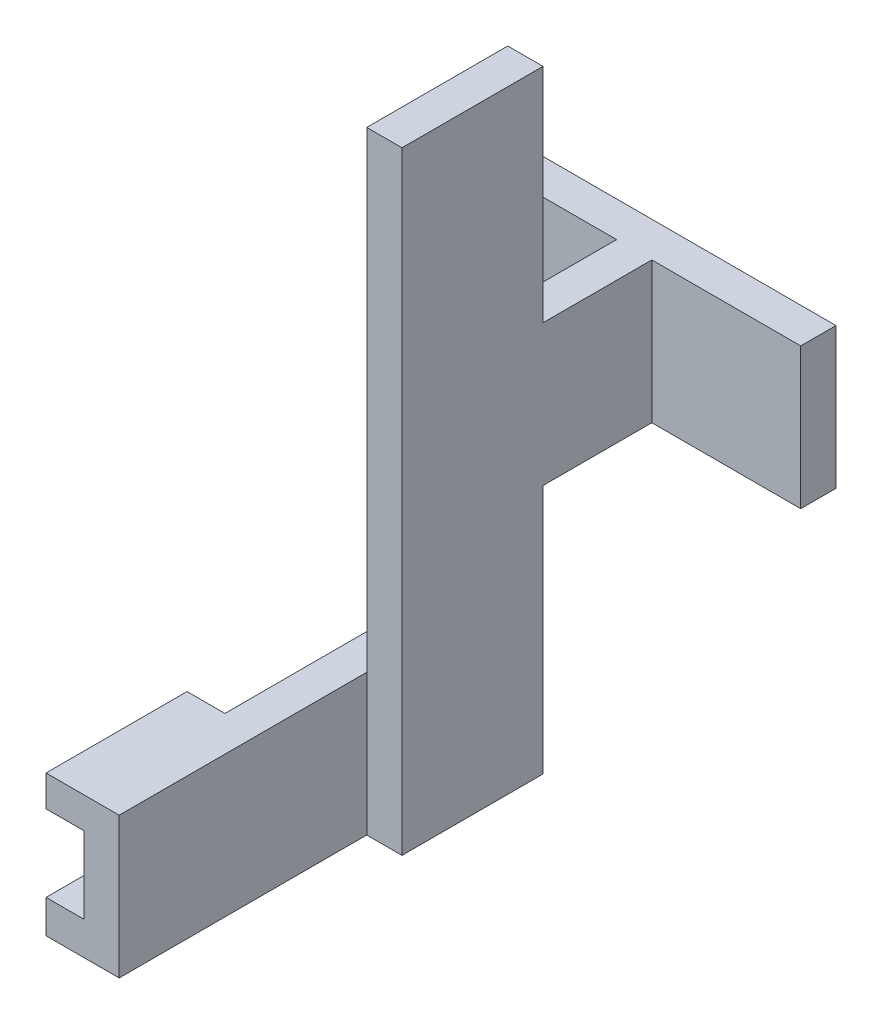
SolidWorks part; units mm, degrees
material "Aleación 1060"
ref_plane "Alzado" through (0, 0, 0) normal (0, 0, 1) x (1, 0, 0)
ref_plane "Planta" through (0, 0, 0) normal (0, 1, 0) x (1, 0, 0)
ref_plane "Vista lateral" through (0, 0, 0) normal (1, 0, 0) x (0, 0, -1)
sketch "Croquis1" plane through (0, 0, 0) normal (0, 0, 1) x (1, 0, 0)
  line L1 (60, -25.4) -> (-60, -25.4)
  line L2 (60, -25.4) -> (60, 25.4)
  line L3 (60, 25.4) -> (-60, 25.4)
  line L4 (-60, -25.4) -> (-60, 25.4)
  line L5 (60, -25.4) -> (-60, 25.4) construction
  line L6 (60, 25.4) -> (-60, -25.4) construction
  point P0 (0, 0)
  dimension "D1" = 50.8
  dimension "D2" = 120
extrude "Saliente-Extruir1" add sketch "Croquis1" along normal blind 12.7
sketch "Croquis2" plane through (0, 0, 12.7) normal (0, 0, 1) x (1, 0, 0)
  line L0 (60, 25.4) -> (-60, 25.4) construction
  line L1 (6.35, -25.4) -> (-6.35, -25.4)
  line L2 (6.35, -25.4) -> (6.35, 25.4)
  line L3 (6.35, 25.4) -> (-6.35, 25.4)
  line L4 (-6.35, -25.4) -> (-6.35, 25.4)
  line L5 (6.35, -25.4) -> (-6.35, 25.4) construction
  line L6 (6.35, 25.4) -> (-6.35, -25.4) construction
  point P0 (0, 0)
  dimension "D1" = 12.7
extrude "Saliente-Extruir2" add sketch "Croquis2" along normal blind 90
sketch "Croquis3" plane through (0, -25.4, 0) normal (0, -1, 0) x (1, 0, 0)
  line L1 (6.35, 102.7) -> (-6.35, 102.7)
  line L2 (6.35, 102.7) -> (6.35, 51.9)
  line L3 (6.35, 51.9) -> (-6.35, 51.9)
  line L4 (-6.35, 102.7) -> (-6.35, 51.9)
  dimension "D1" = 50.8
extrude "Saliente-Extruir3" add sketch "Croquis3" along normal blind 90
sketch "Croquis4" plane through (-6.35, 0, 0) normal (-1, 0, 0) x (0, 0, 1)
  line L1 (51.9, -115.4) -> (191.9, -115.4)
  line L2 (51.9, -115.4) -> (51.9, -64.6)
  line L3 (51.9, -64.6) -> (191.9, -64.6)
  line L4 (191.9, -115.4) -> (191.9, -64.6)
  dimension "D1" = 50.8
  dimension "D2" = 140
extrude "Saliente-Extruir4" add sketch "Croquis4" along normal blind 12.7
sketch "Croquis5" plane through (-19.05, 0, 0) normal (-1, 0, 0) x (0, 0, 1)
  line L1 (191.9, -115.4) -> (141.1, -115.4)
  line L2 (191.9, -115.4) -> (191.9, -103.4194)
  line L3 (191.9, -103.4194) -> (141.1, -103.4194)
  line L4 (141.1, -115.4) -> (141.1, -103.4194)
  line L5 (191.9, -64.6) -> (141.1, -64.6)
  line L6 (191.9, -64.6) -> (191.9, -75.7938)
  line L7 (191.9, -75.7938) -> (141.1, -75.7938)
  line L8 (141.1, -64.6) -> (141.1, -75.7938)
  dimension "D1" = 50.8
  dimension "D2" = 50.8
extrude "Saliente-Extruir5" add sketch "Croquis5" along normal blind 13.65
sketch "Croquis6" plane through (0, 25.4, 0) normal (0, 1, 0) x (1, 0, 0)
  line L1 (-6.35, -102.7) -> (6.35, -102.7)
  line L2 (-6.35, -102.7) -> (-6.35, -51.9)
  line L3 (-6.35, -51.9) -> (6.35, -51.9)
  line L4 (6.35, -102.7) -> (6.35, -51.9)
  dimension "D1" = 50.8
extrude "Saliente-Extruir6" add sketch "Croquis6" along normal blind 80
